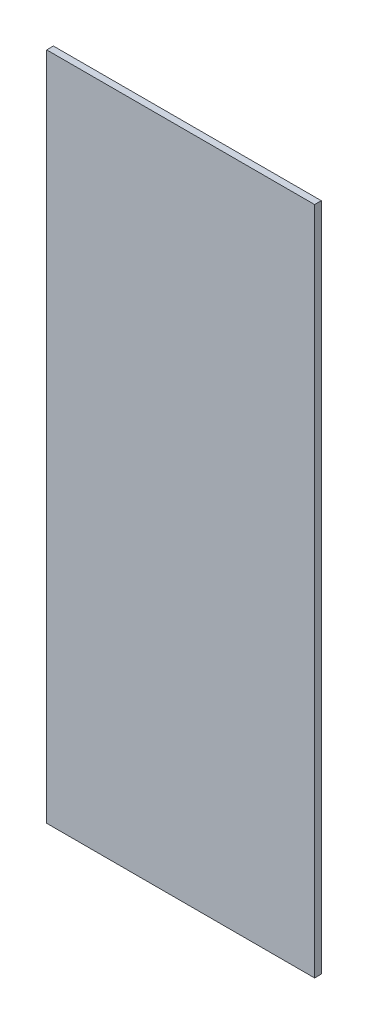
SolidWorks part; units mm, degrees
ref_plane "Front Plane" through (0, 0, 0) normal (1, 0, 0) x (0, 1, 0)
ref_plane "Top Plane" through (0, 0, 0) normal (0, 0, 1) x (0, 1, 0)
ref_plane "Right Plane" through (0, 0, 0) normal (0, 1, 0) x (-1, 0, 0)
sketch "Sketch1" plane through (0, 0, 0) normal (0, 0, 1) x (0, 1, 0)
  line L1 (-158.75, -63.5) -> (158.75, -63.5)
  line L2 (-158.75, -63.5) -> (-158.75, 63.5)
  line L3 (-158.75, 63.5) -> (158.75, 63.5)
  line L4 (158.75, -63.5) -> (158.75, 63.5)
  line L5 (-158.75, -63.5) -> (158.75, 63.5) construction
  line L6 (-158.75, 63.5) -> (158.75, -63.5) construction
  point P1 (0, 0)
  dimension "D1" = 317.5
  dimension "D2" = 127
extrude "Boss-Extrude1" add sketch "Sketch1" along normal blind 3.175
